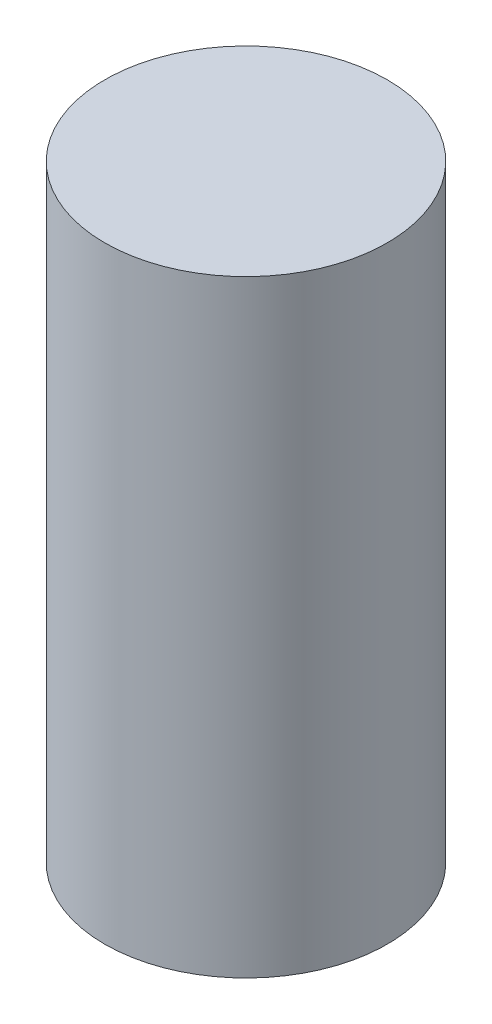
SolidWorks part; units mm, degrees
material "PE High Density"
ref_plane "Front Plane" through (0, 0, 0) normal (0, 0, 1) x (1, 0, 0)
ref_plane "Top Plane" through (0, 0, 0) normal (0, 1, 0) x (1, 0, 0)
ref_plane "Right Plane" through (0, 0, 0) normal (1, 0, 0) x (0, 0, -1)
sketch "Sketch1" plane through (0, 0, 0) normal (0, 1, 0) x (1, 0, 0)
  circle A0 centre (0, 0) radius 50
  dimension "D1" = 100
extrude "Boss-Extrude1" add sketch "Sketch1" along normal blind 215
scale "Scale1" scale about centroid uniform scaling yes scale factor 0.75
